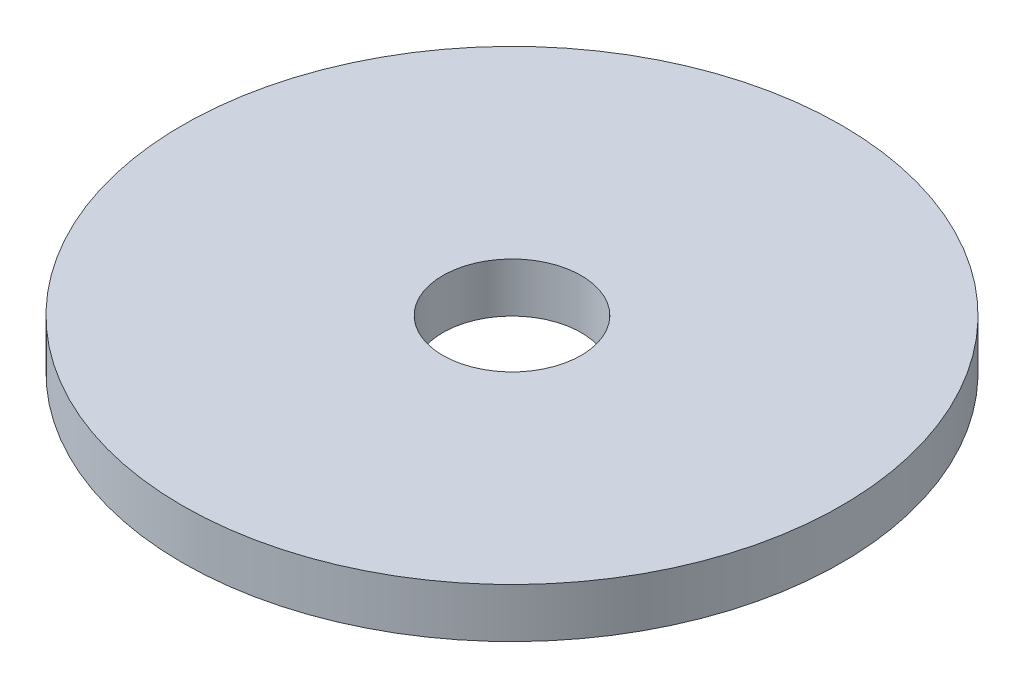
SolidWorks part; units mm, degrees
ref_plane "Спереди" through (0, 0, 0) normal (0, 0, 1) x (1, 0, 0)
ref_plane "Сверху" through (0, 0, 0) normal (0, 1, 0) x (1, 0, 0)
ref_plane "Справа" through (0, 0, 0) normal (1, 0, 0) x (0, 0, -1)
other "Configuration Table"
sketch "Sketch1" plane through (0, 0, 0) normal (0, 1, 0) x (1, 0, 0)
  circle A0 centre (0, 0) radius 10
  circle A1 centre (0, 0) radius 2.1
  dimension "D1" = 4.2
  dimension "D2" = 20
extrude "Boss-Extrude1" add sketch "Sketch1" along normal blind 1.5
